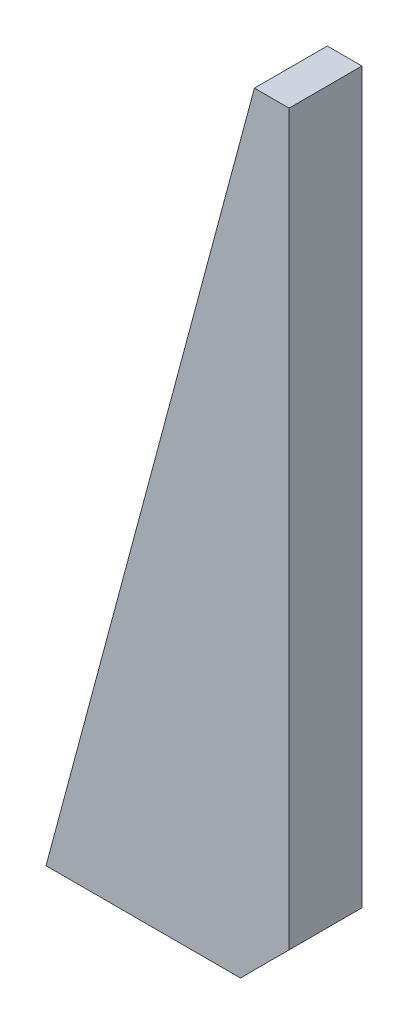
SolidWorks part; units mm, degrees
ref_plane "Front Plane" through (0, 0, 0) normal (0, 0, 1) x (1, 0, 0)
ref_plane "Top Plane" through (0, 0, 0) normal (0, 1, 0) x (1, 0, 0)
ref_plane "Right Plane" through (0, 0, 0) normal (1, 0, 0) x (0, 0, -1)
sketch "Sketch1" plane through (0, 0, 0) normal (0, 0, 1) x (1, 0, 0)
  line L0 (0, 0) -> (0, 160)
  line L1 (0, 0) -> (-50, 0)
  line L2 (-50, 0) -> (-16.4253, 125.3024)
  line L3 (-16.4253, 125.3024) -> (-7.1281, 160)
  line L4 (0, 160) -> (-7.1281, 160)
  dimension "D1" = 160
  dimension "D2" = 50
  dimension "D3" = 75
extrude "Boss-Extrude1" add sketch "Sketch1" along normal blind 15
chamfer "Chamfer1" distance 10 angle 45 1 edges at (0, 0, 7.5)
